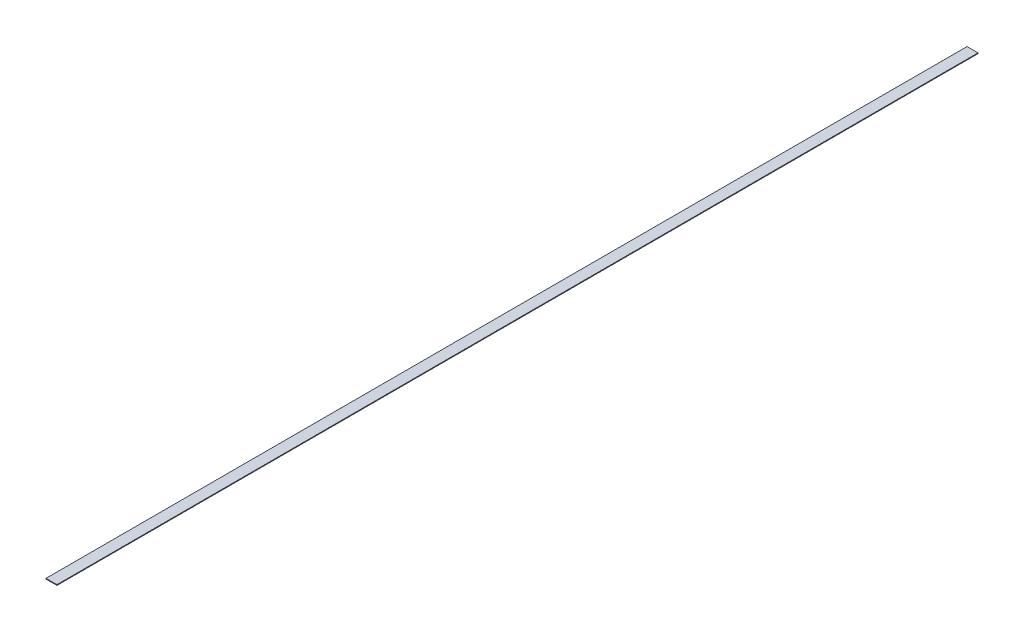
SolidWorks part; units mm, degrees
ref_plane "Front Plane" through (0, 0, 0) normal (0, 0, 1) x (1, 0, 0)
ref_plane "Top Plane" through (0, 0, 0) normal (0, 1, 0) x (1, 0, 0)
ref_plane "Right Plane" through (0, 0, 0) normal (1, 0, 0) x (0, 0, -1)
sketch "Sketch1" plane through (0, 0, 0) normal (0, 0, 1) x (1, 0, 0)
  line L1 (25.4, -1.5875) -> (-25.4, -1.5875)
  line L2 (25.4, -1.5875) -> (25.4, 1.5875)
  line L3 (25.4, 1.5875) -> (-25.4, 1.5875)
  line L4 (-25.4, -1.5875) -> (-25.4, 1.5875)
  line L5 (25.4, -1.5875) -> (-25.4, 1.5875) construction
  line L6 (25.4, 1.5875) -> (-25.4, -1.5875) construction
  circle A0 centre (0, 0) radius 3.175 construction
  dimension "D1" = 6.35
  dimension "D2" = 50.8
  dimension "D3" = 3.175
extrude "Extrude1" add sketch "Sketch1" along normal blind 4267.2
sketch "Sketch2" [suppressed] plane through (0, 0, 0) normal (0, 0, -1) x (-1, 0, 0)
  point P0 (0, 0)
sketch "Sketch3" [suppressed] plane through (0, 0, 4572) normal (0, 0, 1) x (1, 0, 0)
  point P0 (0, 0)
